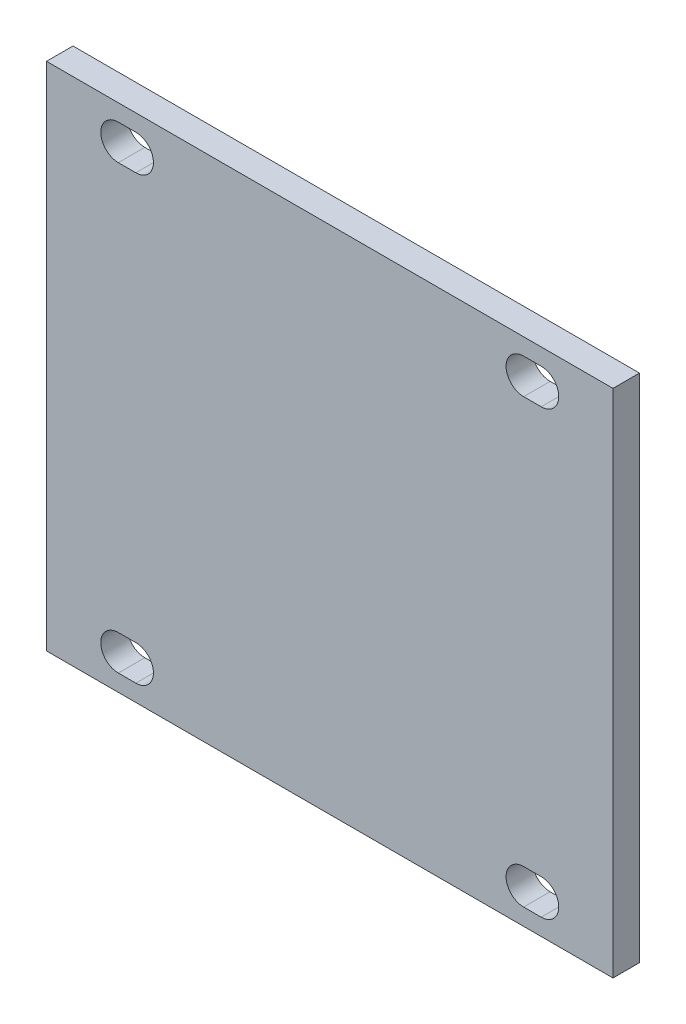
SolidWorks part; units mm, degrees
ref_plane "Front Plane" through (0, 0, 0) normal (0, 0, 1) x (1, 0, 0)
ref_plane "Top Plane" through (0, 0, 0) normal (0, 1, 0) x (1, 0, 0)
ref_plane "Right Plane" through (0, 0, 0) normal (1, 0, 0) x (0, 0, -1)
sketch "Sketch1" plane through (0, 0, 0) normal (0, 0, 1) x (1, 0, 0)
  line L0 (4.5, 29.85) -> (5.6, 29.85) construction
  line L1 (0, 0) -> (35.5, 0)
  line L2 (0, 0) -> (0, 32)
  line L3 (0, 32) -> (35.5, 32)
  line L4 (35.5, 0) -> (35.5, 32)
  line L9 (4.5, 30.95) -> (5.6, 30.95)
  line L10 (4.5, 28.75) -> (5.6, 28.75)
  line L11 (29.9, 28.75) -> (31, 28.75)
  line L12 (29.9, 30.95) -> (31, 30.95)
  line L13 (29.9, 29.85) -> (31, 29.85) construction
  line L14 (29.9, 1.05) -> (31, 1.05)
  line L15 (29.9, 3.25) -> (31, 3.25)
  line L16 (29.9, 2.15) -> (31, 2.15) construction
  line L17 (4.5, 1.05) -> (5.6, 1.05)
  line L18 (4.5, 3.25) -> (5.6, 3.25)
  line L19 (4.5, 2.15) -> (5.6, 2.15) construction
  arc A0 (4.5, 30.95) -> (4.5, 28.75) centre (4.5, 29.85) ccw
  arc A1 (5.6, 28.75) -> (5.6, 30.95) centre (5.6, 29.85) ccw
  arc A2 (29.9, 30.95) -> (29.9, 28.75) centre (29.9, 29.85) ccw
  arc A3 (31, 28.75) -> (31, 30.95) centre (31, 29.85) ccw
  arc A4 (29.9, 3.25) -> (29.9, 1.05) centre (29.9, 2.15) ccw
  arc A5 (31, 1.05) -> (31, 3.25) centre (31, 2.15) ccw
  arc A6 (4.5, 3.25) -> (4.5, 1.05) centre (4.5, 2.15) ccw
  arc A7 (5.6, 1.05) -> (5.6, 3.25) centre (5.6, 2.15) ccw
  point P7 (5.05, 29.85)
  point P16 (30.45, 29.85)
  point P23 (30.45, 2.15)
  point P30 (5.05, 2.15)
  dimension "D3" = 3.3
  dimension "D4" = 1.1
  dimension "D1" = 35.5
  dimension "D2" = 32
  dimension "D5" = 2.15
  dimension "D6" = 5.05
  dimension "D7" = 2
  dimension "D8" = 2
extrude "Boss-Extrude1" add sketch "Sketch1" along normal blind 1.66
sketch "Sketch2" plane through (0, 0, 0) normal (0, 0, 1) x (1, 0, 0)
  line L0 (35.5, 32) -> (0, 32) construction
  line L1 (33.41, 25.86) -> (2.09, 25.86)
  line L2 (33.41, 25.86) -> (33.41, 10.24)
  line L3 (33.41, 10.24) -> (2.09, 10.24)
  line L4 (2.09, 25.86) -> (2.09, 10.24)
  line L5 (35.5, 0) -> (35.5, 32) construction
  point P4 (32.6783, 26.2186)
  dimension "D1" = 31.32
  dimension "D2" = 15.62
  dimension "D3" = 6.14
  dimension "D4" = 2.09
extrude "Boss-Extrude2" add sketch "Sketch2" against normal blind 1
